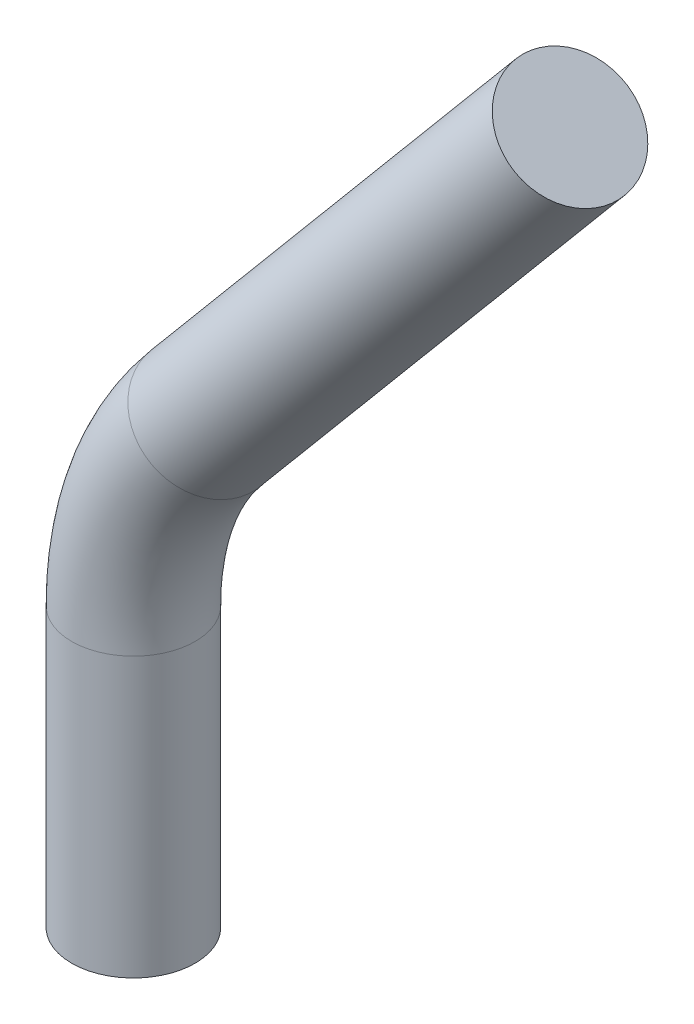
SolidWorks part; units mm, degrees
ref_plane "Front Plane" through (0, 0, 0) normal (0, 0, 1) x (1, 0, 0)
ref_plane "Top Plane" through (0, 0, 0) normal (0, 1, 0) x (1, 0, 0)
ref_plane "Right Plane" through (0, 0, 0) normal (1, 0, 0) x (0, 0, -1)
sketch "Sketch1" plane through (0, 0, 0) normal (0, 0, 1) x (1, 0, 0)
  line L0 (0, 0) -> (0, 13.5404)
  line L1 (3.5093, 23.1823) -> (21.212, 44.2795)
  arc A0 (0, 13.5404) -> (3.5093, 23.1823) centre (15, 13.5404) cw
  point P6 (0, 19)
  dimension "D3" = 15
  dimension "D1" = 33
  dimension "D2" = 19
  dimension "D4" = 140
sketch "Sketch2" plane through (0, 0, 0) normal (0, 1, 0) x (1, 0, 0)
  circle A0 centre (0, 0) radius 3
  dimension "D1" = 6
sketch "Sketch3" plane through (0, 0, 0) normal (0, 0, 1) x (1, 0, 0)
  circle A0 centre (4, 0) radius 0.5
  dimension "D1" = 1
  dimension "D2" = 4
sweep "Sweep1" add profiles "Sketch2" path "Sketch1"
